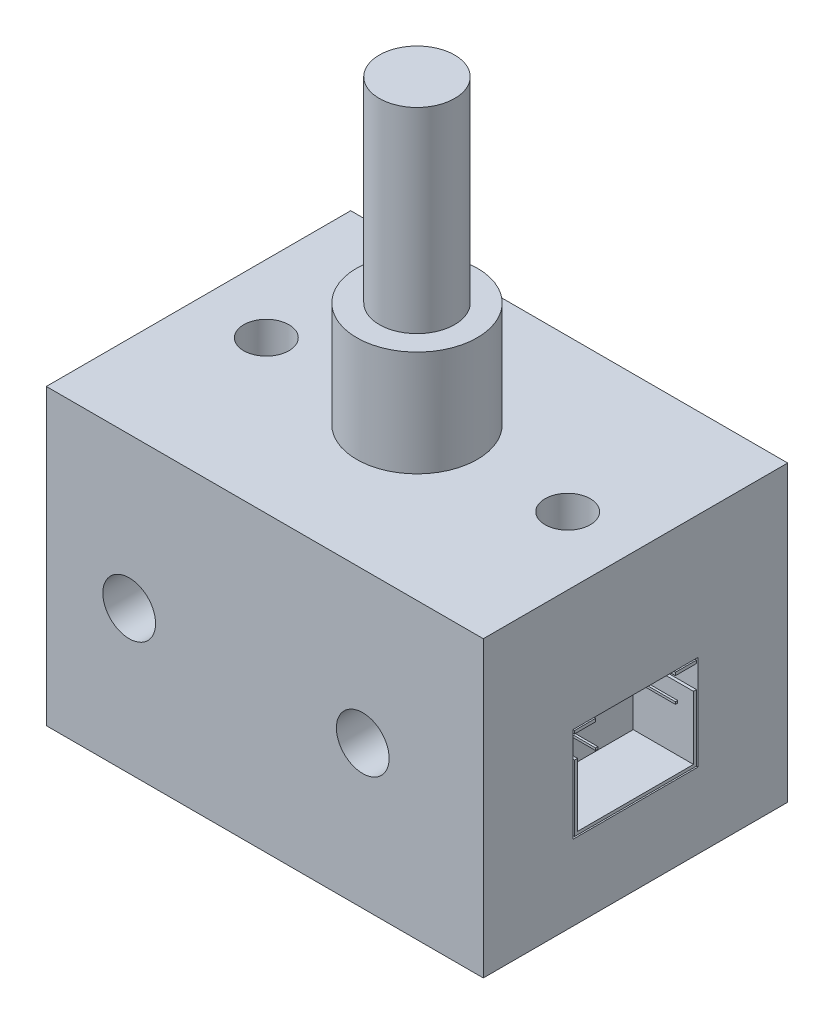
SolidWorks part; units mm, degrees
ref_plane "Front Plane" through (0, 0, 0) normal (0, 0, 1) x (1, 0, 0)
ref_plane "Top Plane" through (0, 0, 0) normal (0, 1, 0) x (1, 0, 0)
ref_plane "Right Plane" through (0, 0, 0) normal (1, 0, 0) x (0, 0, -1)
sketch "Sketch1" plane through (0, 0, 0) normal (0, 0, 1) x (1, 0, 0)
  line L1 (0, 0) -> (29, 0)
  line L2 (0, 0) -> (0, 19.5)
  line L3 (0, 19.5) -> (29, 19.5)
  line L4 (29, 0) -> (29, 19.5)
  circle A0 centre (5.5, 9.5) radius 1.75
  circle A1 centre (21, 9.5) radius 1.75
  dimension "D3" = 3.5
  dimension "D1" = 29
  dimension "D2" = 19.5
  dimension "D4" = 5.5
  dimension "D5" = 8
  dimension "D6" = 9.5
extrude "FrontProfileBoss-Extrude1" add sketch "Sketch1" along normal blind 20.2
sketch "Sketch2" plane through (0, 19.5, 0) normal (0, 1, 0) x (1, 0, 0)
  line L2 (0, -20.2) -> (0, 0) construction
  circle A0 centre (4.5, -10.1) radius 1.5
  circle A1 centre (24.5, -10.1) radius 1.5
  dimension "D2" = 3
  dimension "D1" = 10.1
  dimension "D3" = 20
  dimension "D4" = 4.5
extrude "TopMountingHolesCut-Extrude1" cut sketch "Sketch2" against normal offset from surface (4 mm away) 4 up to face at (14.5, 19.5, 10.1)
sketch "Sketch3" plane through (0, 19.5, 0) normal (0, 1, 0) x (1, 0, 0)
  circle A0 centre (14.5, -10.1) radius 4
  dimension "D1" = 8
  dimension "D2" = 10
extrude "ConningTowerBoss-Extrude2" add sketch "Sketch3" along normal blind 7
sketch "Sketch4" plane through (0, 26.5, 0) normal (0, 1, 0) x (1, 0, 0)
  circle A0 centre (14.5, -10.1) radius 2.5
  dimension "D1" = 5
extrude "PlungerBoss-Extrude3" add sketch "Sketch4" along normal blind 13
sketch "Sketch5" plane through (0, 0, 0) normal (0, 0, -1) x (-1, 0, 0)
  circle A0 centre (-21, 9.5) radius 3
  circle A1 centre (-5.5, 9.5) radius 3
  circle A2 centre (-5.5, 9.5) radius 1.75 construction
  circle A3 centre (-21, 9.5) radius 1.75 construction
  dimension "D1" = 6
extrude "BackMountingHolesBorCut-Extrude2" cut sketch "Sketch5" against normal offset from surface (6 mm away) 6 up to face at (7.25, 9.5, 0)
sketch "Sketch6" plane through (29, 0, 0) normal (1, 0, 0) x (0, 0, -1)
  line L0 (-20.2, 0) -> (-20.2, 19.5) construction
  line L1 (-14.25, 11.3) -> (-5.95, 11.3)
  line L2 (-14.25, 11.3) -> (-14.25, 5)
  line L3 (-14.25, 5) -> (-5.95, 5)
  line L4 (-5.95, 11.3) -> (-5.95, 5)
  line L5 (-20.2, 0) -> (0, 0) construction
  dimension "D1" = 8.3
  dimension "D2" = 6.3
  dimension "D3" = 5.95
  dimension "D4" = 5
extrude "XHTerminalCut-Extrude14" cut sketch "Sketch6" against normal blind 4
sketch "Sketch7" plane through (25, 0, 0) normal (1, 0, 0) x (0, 0, -1)
  line L0 (-14.15, 9.5) -> (-14.15, 5.1)
  line L1 (-14.15, 5.1) -> (-6.05, 5.1)
  line L2 (-6.05, 5.1) -> (-6.05, 9.5)
  line L3 (-20.2, 9.5) -> (-6, 9.5) construction
  line L4 (-6.05, 9.5) -> (-6.25, 9.5)
  line L5 (-6.25, 9.5) -> (-6.25, 5.3)
  line L6 (-6.25, 5.3) -> (-13.95, 5.3)
  line L7 (-13.95, 5.3) -> (-13.95, 9.5)
  line L8 (-13.95, 9.5) -> (-14.15, 9.5)
  line L9 (-14.15, 11.2) -> (-12.75, 11.2)
  line L10 (-12.75, 11.2) -> (-12.75, 11)
  line L11 (-12.75, 11) -> (-14.15, 11)
  line L12 (-14.15, 11) -> (-14.15, 11.2)
  line L13 (-7.45, 11.2) -> (-6.05, 11.2)
  line L14 (-6.05, 11.2) -> (-6.05, 11)
  line L15 (-6.05, 11) -> (-7.45, 11)
  line L16 (-7.45, 11) -> (-7.45, 11.2)
  line L17 (-5.95, 11.3) -> (-14.25, 11.3) construction
  line L18 (-14.25, 11.3) -> (-14.25, 5) construction
  line L19 (-5.95, 5) -> (-5.95, 11.3) construction
  line L20 (-14.25, 5) -> (-5.95, 5) construction
  line L22 (-12.75, 9.5) -> (-12.6, 9.5)
  line L23 (-12.75, 9.5) -> (-12.75, 9.35)
  line L24 (-12.75, 9.35) -> (-12.6, 9.35)
  line L25 (-12.6, 9.5) -> (-12.6, 9.35)
  line L26 (-7.45, 9.5) -> (-7.3, 9.5)
  line L27 (-7.45, 9.5) -> (-7.45, 9.35)
  line L28 (-7.45, 9.35) -> (-7.3, 9.35)
  line L29 (-7.3, 9.5) -> (-7.3, 9.35)
  dimension "D1" = 0.2
  dimension "D2" = 0.1
  dimension "D3" = 0.1
  dimension "D4" = 0.1
  dimension "D5" = 0.1
  dimension "D6" = 0.2
  dimension "D7" = 1.4
  dimension "D8" = 0.15
extrude "XHTerminalBoss-Extrude4" add sketch "Sketch7" along normal blind 4
equation "\"ZEndStopWidth\"= 29mm"
equation "\"D1@Sketch1\"=\"ZEndStopWidth\""
equation "\"ZEndStopHeight\"= 19.5mm"
equation "\"D2@Sketch1\"=\"ZEndStopHeight\""
equation "\"ZEndStopFrontMountingHoleDiameter\"= 3.5mm"
equation "\"D3@Sketch1\"=\"ZEndStopFrontMountingHoleDiameter\""
equation "\"ZEndStopFrontMountingHoleOffsetFromLeftSide\"= 5.5mm"
equation "\"D5@Sketch1\"=\"ZEndStopFrontMountingHoleOffsetFromRightSide\""
equation "\"ZEndStopFrontMountingHoleOffsetFromBottom\"= 9.5mm"
equation "\"D6@Sketch1\"=\"ZEndStopFrontMountingHoleOffsetFromBottom\""
equation "\"D4@Sketch1\"=\"ZEndStopFrontMountingHoleOffsetFromLeftSide\""
equation "\"ZEndStopDepth\"= 20.2mm"
equation "\"D1@FrontProfileBoss-Extrude1\" = \"ZEndStopDepth\""
equation "\"D1@Sketch2\"=\"ZEndStopDepth\"/2"
equation "\"M3ThreadedHoleDiameter\"= 3mm"
equation "\"D2@Sketch2\"=\"M3ThreadedHoleDiameter\""
equation "\"ZEndStopTopMountingHoleDepth\"= 4mm"
equation "\"D1@TopMountingHolesCut-Extrude1\" = \"ZEndStopTopMountingHoleDepth\""
equation "\"ZEndStopTopSwitchConningTowerDiameter\"= 8mm"
equation "\"D1@Sketch3\"=\"ZEndStopTopSwitchConningTowerDiameter\""
equation "\"ZEndStopTopSwitchConningTowerHeigth\"= 7mm"
equation "\"D1@ConningTowerBoss-Extrude2\" = \"ZEndStopTopSwitchConningTowerHeigth\""
equation "\"ZEndStopPlungerDiameter\"=5"
equation "\"D1@Sketch4\"=\"ZEndStopPlungerDiameter\""
equation "\"ZEndStopPlungerHeight\"= 13mm"
equation "\"ZEndStopFrontMountingBoreHoleDiameter\"= 6mm"
equation "\"ZEndStopFrontMountingBoreHoleDepth\"= 6mm"
equation "\"D1@PlungerBoss-Extrude3\" = \"ZEndStopPlungerHeight\""
equation "\"D1@Sketch5\"=\"ZEndStopFrontMountingBoreHoleDiameter\""
equation "\"D1@BackMountingHolesBorCut-Extrude2\" = \"ZEndStopFrontMountingBoreHoleDepth\""
equation "\"XHTerminalWidth\"=8.3"
equation "\"XHTerminalHeight\"=6.3"
equation "\"D2@Sketch6\"=\"XHTerminalHeight\""
equation "\"D3@Sketch6\"=(\"ZEndStopDepth\"-\"XHTerminalWidth\")/2"
equation "\"D1@Sketch6\"=\"XHTerminalWidth\""
equation "\"XHTerminalDepth\"= 4mm"
equation "\"ZEndStopFrontMountingHoleOffsetFromRightSide\"= 8mm"
equation "\"D1@XHTerminalCut-Extrude14\" = \"XHTerminalDepth\""
equation "\"D1@XHTerminalBoss-Extrude4\" = \"XHTerminalDepth\""
equation "\"ZEndStopTopDiistanceBetweenMountingHoles\"=20"
equation "\"D3@Sketch2\"=\"ZEndStopTopDiistanceBetweenMountingHoles\""
equation "\"D4@Sketch2\"=(\"ZEndStopWidth\"-\"ZEndStopTopDiistanceBetweenMountingHoles\")/2"
equation "\"D2@Sketch3\"=\"ZEndStopTopDiistanceBetweenMountingHoles\"/2"
